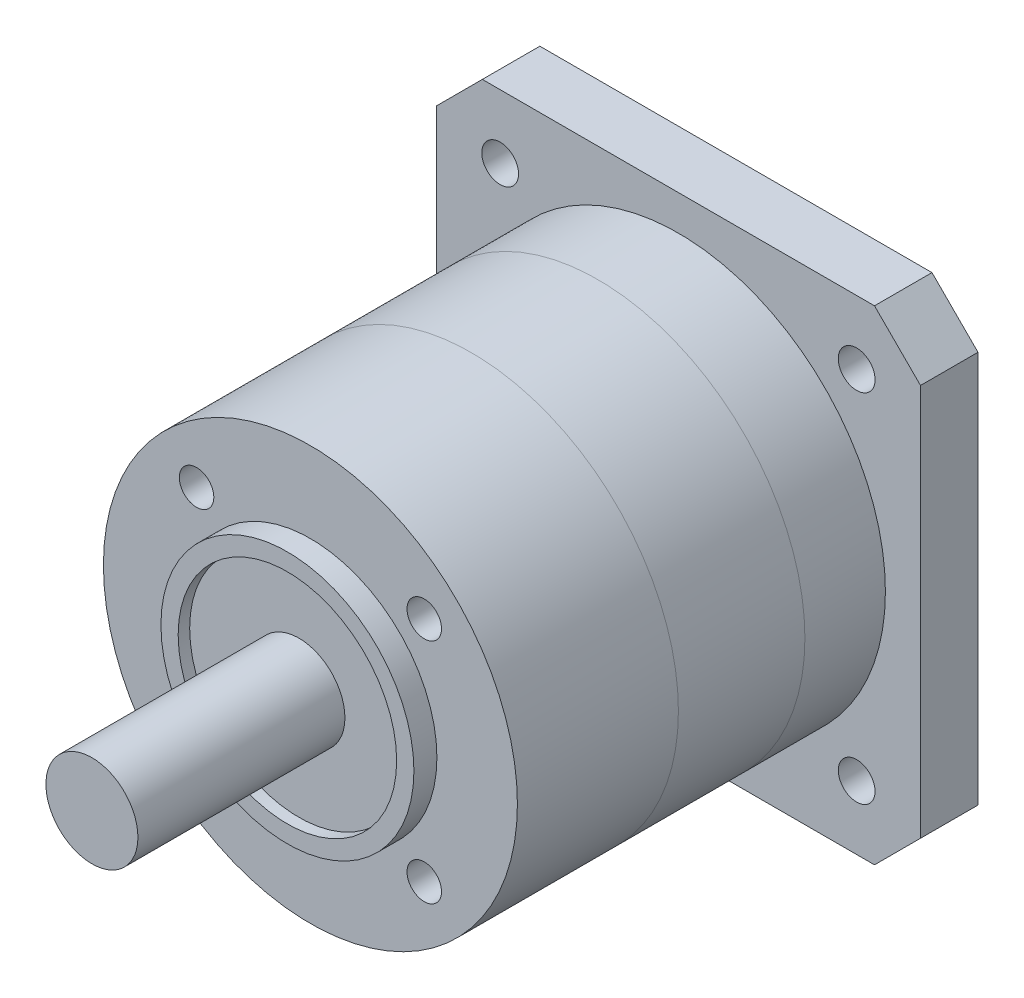
SolidWorks part; units mm, degrees
material "AISI 1020"
ref_plane "Front Plane" through (0, 0, 0) normal (0, 0, 1) x (1, 0, 0)
ref_plane "Top Plane" through (0, 0, 0) normal (0, 1, 0) x (1, 0, 0)
ref_plane "Right Plane" through (0, 0, 0) normal (1, 0, 0) x (0, 0, -1)
sketch "Sketch1" plane through (0, 0, 0) normal (0, 0, 1) x (1, 0, 0)
  line L1 (21.05, -21.05) -> (-21.05, -21.05)
  line L2 (21.05, -21.05) -> (21.05, 21.05)
  line L3 (21.05, 21.05) -> (-21.05, 21.05)
  line L4 (-21.05, -21.05) -> (-21.05, 21.05)
  line L5 (21.05, -21.05) -> (-21.05, 21.05) construction
  line L6 (21.05, 21.05) -> (-21.05, -21.05) construction
  point P0 (0, 0)
  dimension "D1" = 42.1
extrude "Boss-Extrude2" add sketch "Sketch1" along normal blind 5
sketch "Sketch3" plane through (0, 0, 5) normal (0, 0, 1) x (1, 0, 0)
  circle A0 centre (0, 0) radius 18
  dimension "D1" = 36
extrude "Boss-Extrude3" add sketch "Sketch3" along normal offset from surface (7 mm away) 12 up to face at (0, 0, 0)
sketch "Sketch4" plane through (0, 0, 12) normal (0, 0, 1) x (1, 0, 0)
  circle A1 centre (0, 0) radius 18
  circle A2 centre (0, 0) radius 18
  dimension "D1" = 0
extrude "Boss-Extrude4" add sketch "Sketch4" along normal offset from surface (11 mm away) 23 separate body up to face at (0, 0, 0)
sketch "Sketch5" plane through (0, 0, 23) normal (0, 0, 1) x (1, 0, 0)
  circle A1 centre (0, 0) radius 18
  circle A2 centre (0, 0) radius 18
  dimension "D1" = 0
extrude "Boss-Extrude5" add sketch "Sketch5" along normal offset from surface (14 mm away) 37 separate body up to face at (0, 0, 0)
sketch "Sketch6" plane through (0, 0, 37) normal (0, 0, 1) x (1, 0, 0)
  circle A0 centre (0, 0) radius 11
  circle A1 centre (0, 0) radius 9.5 construction
  dimension "D2" = 22
extrude "Boss-Extrude6" add sketch "Sketch6" along normal blind 2
sketch "Sketch9" plane through (0, 0, 39) normal (0, 0, 1) x (1, 0, 0)
  circle A3 centre (0, 0) radius 9.5
  dimension "D1" = 19
extrude "Cut-Extrude2" cut sketch "Sketch9" against normal blind 1
sketch "Sketch7" plane through (0, 0, 37) normal (0, 0, 1) x (1, 0, 0)
  circle A0 centre (0, 0) radius 4
  dimension "D1" = 8
extrude "Boss-Extrude7" add sketch "Sketch7" along normal blind 19 separate body
sketch "Sketch10" plane through (0, 0, 0) normal (0, 0, -1) x (-1, 0, 0)
  line L1 (15.5, -15.5) -> (-15.5, -15.5) construction
  line L2 (15.5, -15.5) -> (15.5, 15.5) construction
  line L3 (15.5, 15.5) -> (-15.5, 15.5) construction
  line L4 (-15.5, -15.5) -> (-15.5, 15.5) construction
  line L5 (15.5, -15.5) -> (-15.5, 15.5) construction
  line L6 (15.5, 15.5) -> (-15.5, -15.5) construction
  circle A0 centre (-15.5, 15.5) radius 1.6
  circle A1 centre (15.5, 15.5) radius 1.6
  circle A2 centre (15.5, -15.5) radius 1.6
  circle A3 centre (-15.5, -15.5) radius 1.6
  point P0 (0, 0)
  dimension "D2" = 3.2
  dimension "D1" = 31
extrude "Cut-Extrude3" cut sketch "Sketch10" against normal up to next (5 mm away)
sketch "Sketch12" plane through (0, 0, 37) normal (0, 0, 1) x (1, 0, 0)
  line L0 (-9.8995, 9.8995) -> (0, 0) construction
  line L1 (0, 0) -> (0, 14) construction
  circle A4 centre (0, 0) radius 14 construction
  circle A5 centre (-9.8995, 9.8995) radius 1.5
  circle A6 centre (9.8995, 9.8995) radius 1.5
  circle A7 centre (9.8995, -9.8995) radius 1.5
  circle A8 centre (-9.8995, -9.8995) radius 1.5
  point P4 (21.8146, 12.3744)
  point P12 (0, 0)
  point P14 (0, 0)
  dimension "D1" = 28
  dimension "D3" = 3
  dimension "D2" = 4
  dimension "D4" = 45
extrude "Cut-Extrude5" cut sketch "Sketch12" against normal blind 10
chamfer "Chamfer1" distance 4 angle 45 4 edges at (21.05, -21.05, 2.5) (-21.05, -21.05, 2.5) (21.05, 21.05, 2.5) (-21.05, 21.05, 2.5)
sketch "Sketch15" plane through (0, 0, 0) normal (0, 0, -1) x (-1, 0, 0)
  circle A0 centre (0, 0) radius 11
  dimension "D1" = 22
extrude "Cut-Extrude8" cut sketch "Sketch15" against normal blind 1.5
